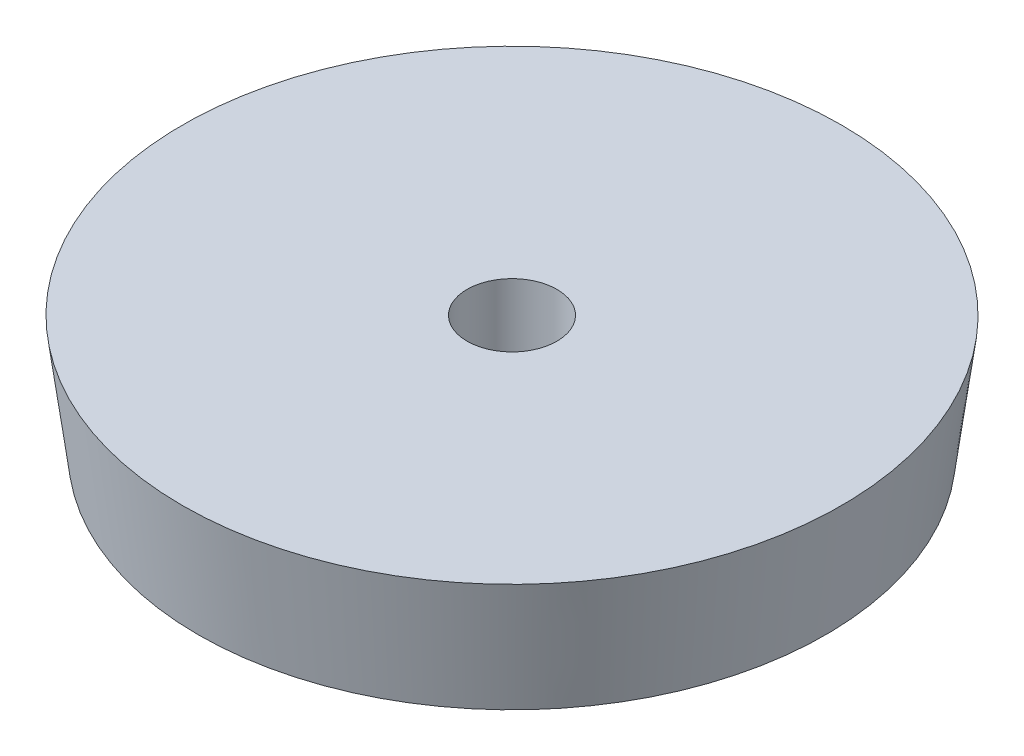
SolidWorks part; units mm, degrees
ref_plane "Front Plane" through (0, 0, 0) normal (0, 0, 1) x (1, 0, 0)
ref_plane "Top Plane" through (0, 0, 0) normal (0, 1, 0) x (1, 0, 0)
ref_plane "Right Plane" through (0, 0, 0) normal (1, 0, 0) x (0, 0, -1)
sketch "Sketch1" plane through (0, 0, 0) normal (0, 1, 0) x (1, 0, 0)
  circle A0 centre (0, 0) radius 104.775
  dimension "D1" = 209.55
extrude "Boss-Extrude1" add sketch "Sketch1" against normal blind 38.1 draft 7.5
sketch "Sketch2" plane through (0, 0, 0) normal (0, 1, 0) x (1, 0, 0)
  circle A0 centre (0, 0) radius 14.2875
  dimension "D1" = 28.575
extrude "Cut-Extrude1" cut sketch "Sketch2" against normal through all
